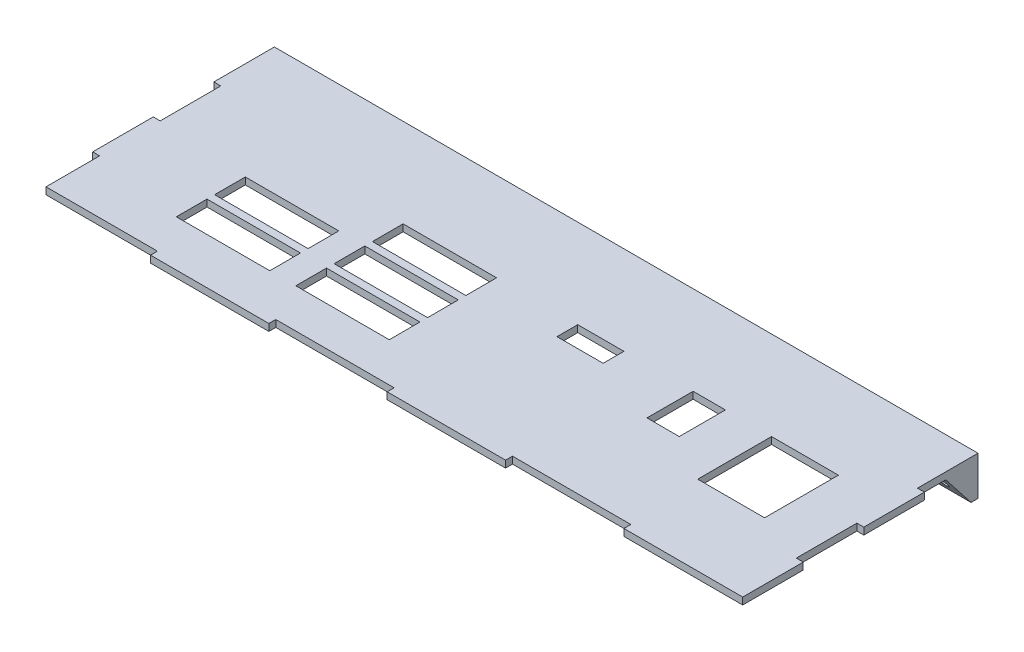
SolidWorks part; units mm, degrees
ref_plane "Спереди" through (0, 0, 0) normal (0, 0, 1) x (1, 0, 0)
ref_plane "Сверху" through (0, 0, 0) normal (0, 1, 0) x (1, 0, 0)
ref_plane "Справа" through (0, 0, 0) normal (1, 0, 0) x (0, 0, -1)
other "Configuration Table"
sketch "Эскиз1" plane through (0, 0, 0) normal (0, 1, 0) x (1, 0, 0)
  line L0 (-121.424, 15.1446) -> (-121.424, 41.3946)
  line L1 (-118.424, -63.6054) -> (186.576, -63.6054)
  line L2 (-121.424, -37.3554) -> (-121.424, -11.1054)
  line L3 (-121.424, 41.3946) -> (183.576, 41.3946)
  line L4 (186.576, -63.6054) -> (186.576, -37.3554)
  line L5 (-118.424, -62.7765) -> (183.576, 97.3135) construction
  line L6 (-121.424, 41.3946) -> (186.576, -63.6054) construction
  line L11 (-121.424, 15.1446) -> (-118.424, 15.1446)
  line L13 (-121.424, -11.1054) -> (-118.424, -11.1054)
  line L14 (-118.424, 15.1446) -> (-118.424, -11.1054)
  line L15 (-121.424, -37.3554) -> (-118.424, -37.3554)
  line L18 (-118.424, -37.3554) -> (-118.424, -63.6054)
  line L21 (186.576, 15.1446) -> (183.576, 15.1446)
  line L22 (183.576, 41.3946) -> (183.576, 15.1446)
  line L23 (186.576, -37.3554) -> (183.576, -37.3554)
  line L25 (186.576, -11.1054) -> (183.576, -11.1054)
  line L26 (183.576, -37.3554) -> (183.576, -11.1054)
  line L27 (186.576, -11.1054) -> (186.576, 15.1446)
  point P0 (0, 0)
  dimension "D1" = 308
  dimension "D2" = 105
  dimension "D3" = 26.25
  dimension "D4" = 26.25
  dimension "D5" = 3
extrude "Бобышка-Вытянуть1" add sketch "Эскиз1" along normal blind 3
sketch "Эскиз2" plane through (0, 3, 0) normal (0, 1, 0) x (1, 0, 0)
  line L0 (-118.424, -63.6054) -> (186.576, -63.6054) construction
  line L1 (-78.924, -43.6054) -> (-38.424, -43.6054)
  line L2 (-78.924, -43.6054) -> (-78.924, -30.3054)
  line L3 (-78.924, -30.3054) -> (-38.424, -30.3054)
  line L4 (-38.424, -43.6054) -> (-38.424, -30.3054)
  line L5 (-121.424, -11.1054) -> (-121.424, -37.3554) construction
  line L6 (-27.124, -43.6054) -> (13.376, -43.6054)
  line L7 (-27.124, -43.6054) -> (-27.124, -30.3054)
  line L8 (-27.124, -30.3054) -> (13.376, -30.3054)
  line L9 (13.376, -43.6054) -> (13.376, -30.3054)
  line L10 (-27.124, -27.0054) -> (13.376, -27.0054)
  line L11 (-27.124, -27.0054) -> (-27.124, -13.7054)
  line L12 (-27.124, -13.7054) -> (13.376, -13.7054)
  line L13 (13.376, -27.0054) -> (13.376, -13.7054)
  line L14 (-78.924, -27.0054) -> (-38.424, -27.0054)
  line L15 (-78.924, -27.0054) -> (-78.924, -13.7054)
  line L16 (-78.924, -13.7054) -> (-38.424, -13.7054)
  line L17 (-38.424, -27.0054) -> (-38.424, -13.7054)
  line L18 (-27.124, -10.4054) -> (13.376, -10.4054)
  line L19 (-27.124, -10.4054) -> (-27.124, 2.8946)
  line L20 (-27.124, 2.8946) -> (13.376, 2.8946)
  line L21 (13.376, -10.4054) -> (13.376, 2.8946)
  line L23 (48.576, -6.1054) -> (68.576, -6.1054)
  line L24 (48.576, -6.1054) -> (48.576, 2.8946)
  line L25 (48.576, 2.8946) -> (68.576, 2.8946)
  line L26 (68.576, -6.1054) -> (68.576, 2.8946)
  line L27 (48.576, -6.1054) -> (68.576, 2.8946) construction
  line L28 (48.576, 2.8946) -> (68.576, -6.1054) construction
  line L30 (98.576, -17.1054) -> (112.576, -17.1054)
  line L31 (98.576, -17.1054) -> (98.576, 2.8946)
  line L32 (98.576, 2.8946) -> (112.576, 2.8946)
  line L33 (112.576, -17.1054) -> (112.576, 2.8946)
  line L34 (98.576, -17.1054) -> (112.576, 2.8946) construction
  line L35 (98.576, 2.8946) -> (112.576, -17.1054) construction
  line L37 (132.576, -29.1054) -> (161.576, -29.1054)
  line L38 (132.576, -29.1054) -> (132.576, 2.8946)
  line L39 (132.576, 2.8946) -> (161.576, 2.8946)
  line L40 (161.576, -29.1054) -> (161.576, 2.8946)
  line L41 (132.576, -29.1054) -> (161.576, 2.8946) construction
  line L42 (132.576, 2.8946) -> (161.576, -29.1054) construction
  point P6 (-78.924, -36.9554)
  point P9 (58.576, -1.6054)
  point P30 (105.576, -7.1054)
  point P35 (147.076, -13.1054)
  dimension "D1" = 40.5
  dimension "D2" = 13.3
  dimension "D3" = 20
  dimension "D4" = 42.5
  dimension "D7" = 3.3
  dimension "D8" = 11.3
  dimension "D10" = 20
  dimension "D11" = 9
  dimension "D12" = 170
  dimension "D13" = 20
  dimension "D14" = 14
  dimension "D15" = 20
  dimension "D16" = 30
  dimension "D17" = 29
  dimension "D18" = 32
  dimension "D19" = 3.3
  dimension "D6" = 2
  dimension "D5" = 2
  dimension "D9" = 2
extrude "Вырез-Вытянуть1" cut sketch "Эскиз2" against normal blind 3
sketch "Эскиз3" plane through (0, 3, 0) normal (0, 1, 0) x (1, 0, 0)
  line L0 (-118.424, -63.6054) -> (186.576, -63.6054) construction
  line L1 (-70.124, -63.6054) -> (-121.424, -63.6054)
  line L2 (-70.124, -63.6054) -> (-70.124, -60.6054)
  line L3 (-70.124, -60.6054) -> (-121.424, -60.6054)
  line L4 (-121.424, -63.6054) -> (-121.424, -60.6054)
  line L5 (-121.424, -11.1054) -> (-121.424, -37.3554) construction
  line L7 (-18.824, -63.6054) -> (32.476, -63.6054)
  line L8 (-18.824, -63.6054) -> (-18.824, -60.6054)
  line L9 (-18.824, -60.6054) -> (32.476, -60.6054)
  line L10 (32.476, -63.6054) -> (32.476, -60.6054)
  line L11 (83.776, -63.6054) -> (135.076, -63.6054)
  line L12 (83.776, -63.6054) -> (83.776, -60.6054)
  line L13 (83.776, -60.6054) -> (135.076, -60.6054)
  line L14 (135.076, -63.6054) -> (135.076, -60.6054)
  dimension "D1" = 51.3
  dimension "D2" = 3
  dimension "D3" = 51.3
  dimension "D4" = 51.3
extrude "Вырез-Вытянуть2" cut sketch "Эскиз3" against normal blind 3
sketch "Эскиз4" plane through (0, 0, 0) normal (0, -1, 0) x (1, 0, 0)
  line L0 (-118.424, -15.1446) -> (-118.424, -41.3946) construction
  line L1 (183.576, -41.3946) -> (-121.424, -41.3946) construction
  line L2 (25.576, -13.3946) -> (29.576, -13.3946)
  line L3 (-118.424, -41.3946) -> (-104.424, -41.3946)
  line L4 (-118.424, -41.3946) -> (-118.424, -27.3946)
  line L5 (-118.424, -27.3946) -> (-104.424, -27.3946)
  line L6 (-104.424, -41.3946) -> (-104.424, -27.3946)
  line L7 (183.576, -41.3946) -> (169.576, -41.3946)
  line L8 (183.576, -41.3946) -> (183.576, -27.3946)
  line L9 (183.576, -27.3946) -> (169.576, -27.3946)
  line L10 (169.576, -41.3946) -> (169.576, -27.3946)
  line L11 (35.576, -13.3946) -> (39.576, -13.3946)
  line L13 (25.576, -41.3946) -> (29.576, -41.3946)
  line L14 (25.576, -41.3946) -> (25.576, -13.3946)
  line L16 (39.576, -41.3946) -> (39.576, -13.3946)
  line L17 (35.576, -13.3946) -> (35.576, -41.3946)
  line L19 (29.576, -13.3946) -> (29.576, -41.3946)
  line L20 (35.576, -41.3946) -> (39.576, -41.3946)
  dimension "D1" = 14
  dimension "D2" = 14
  dimension "D3" = 130
  dimension "D4" = 28
  dimension "D5" = 4
  dimension "D6" = 4
  dimension "D7" = 14
extrude "Бобышка-Вытянуть2" add sketch "Эскиз4" along normal blind 14
sketch "Эскиз6" plane through (39.576, 0, 0) normal (1, 0, 0) x (0, 0, -1)
  line L1 (41.3946, -14) -> (13.3946, -14) construction
  line L4 (13.3946, -14) -> (13.3946, 0)
  line L5 (13.3946, 0) -> (38.3946, -14)
  line L6 (13.3946, -14) -> (38.3946, -14)
  dimension "D1" = 25
extrude "Вырез-Вытянуть3" cut sketch "Эскиз6" against normal blind 14
sketch "Эскиз7" plane through (183.576, 0, 0) normal (1, 0, 0) x (0, 0, -1)
  line L0 (27.3946, -14) -> (27.3946, 0)
  line L1 (27.3946, -14) -> (38.3946, -14)
  line L2 (41.3946, -14) -> (27.3946, -14) construction
  line L3 (38.3946, -14) -> (27.3946, 0)
  dimension "D1" = 11
extrude "Вырез-Вытянуть4" cut sketch "Эскиз7" against normal blind 14
sketch "Эскиз8" plane through (-104.424, 0, 0) normal (1, 0, 0) x (0, 0, -1)
  line L0 (27.3946, -14) -> (27.3946, 0)
  line L1 (41.3946, 0) -> (13.3946, 0) construction
  line L2 (27.3946, 0) -> (38.3946, -14)
  line L3 (38.3946, -14) -> (27.3946, -14)
extrude "Вырез-Вытянуть5" cut sketch "Эскиз8" against normal blind 14
sketch "Эскиз9" plane through (0, 0, -41.3946) normal (0, 0, -1) x (-1, 0, 0)
  line L0 (-169.576, -14) -> (-183.576, -14) construction
  line L1 (-183.576, 3) -> (-183.576, -14) construction
  line L2 (118.424, -14) -> (104.424, -14) construction
  line L3 (104.424, -14) -> (104.424, 0) construction
  circle A0 centre (-176.576, -7) radius 2.5
  circle A1 centre (111.424, -7) radius 2.5
  dimension "D3" = 5
  dimension "D4" = 5
  dimension "D1" = 7
  dimension "D2" = 7
  dimension "D5" = 7
  dimension "D6" = 7
extrude "Вырез-Вытянуть6" cut sketch "Эскиз9" against normal up to vertex up to point (169.576, 0, -27.3945)
